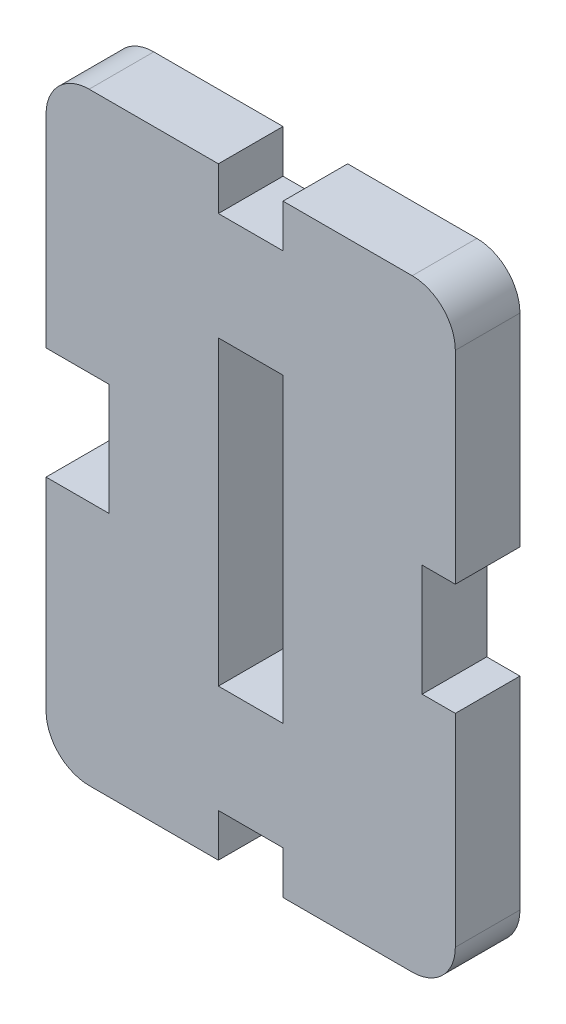
SolidWorks part; units mm, degrees
ref_plane "Front" through (0, 0, 0) normal (0, 0, 1) x (1, 0, 0)
ref_plane "Top" through (0, 0, 0) normal (0, 1, 0) x (1, 0, 0)
ref_plane "Right" through (0, 0, 0) normal (1, 0, 0) x (0, 0, -1)
sketch "Sketch1" plane through (0, 0, 0) normal (0, 0, 1) x (1, 0, 0)
  line L0 (-1044.1169, 48.9977) -> (-1044.1169, 34.9977)
  line L1 (-1049.1904, 41.9977) -> (-1034.6577, 41.9977) construction
  line L2 (-1041.1169, 34.9977) -> (-1041.1169, 48.9977)
  line L3 (-1041.1169, 48.9977) -> (-1044.1169, 48.9977)
  line L4 (-1033.1169, 53.9977) -> (-1033.1169, 44.5931)
  line L5 (-1033.1169, 44.5931) -> (-1034.6577, 44.5931)
  line L6 (-1034.6577, 44.5931) -> (-1034.6577, 39.4024)
  line L7 (-1050.1169, 27.9977) -> (-1044.1169, 27.9977)
  line L8 (-1042.6169, 53.9977) -> (-1041.1169, 53.9977)
  line L9 (-1041.1169, 53.9977) -> (-1041.1169, 55.9977)
  line L10 (-1041.1169, 55.9977) -> (-1035.1169, 55.9977)
  line L11 (-1042.6169, 53.9977) -> (-1044.1169, 53.9977)
  line L12 (-1044.1169, 53.9977) -> (-1044.1169, 55.9977)
  line L13 (-1052.1169, 39.4024) -> (-1052.1169, 29.9977)
  line L14 (-1049.1904, 39.4024) -> (-1052.1169, 39.4024)
  line L15 (-1044.1169, 29.9977) -> (-1044.1169, 27.9977)
  line L16 (-1042.6169, 29.9977) -> (-1044.1169, 29.9977)
  line L17 (-1041.1169, 27.9977) -> (-1035.1169, 27.9977)
  line L18 (-1049.1904, 39.4024) -> (-1049.1904, 44.5931)
  line L19 (-1049.1904, 44.5931) -> (-1052.1169, 44.5931)
  line L20 (-1052.1169, 44.5931) -> (-1052.1169, 53.9977)
  line L21 (-1041.1169, 29.9977) -> (-1041.1169, 27.9977)
  line L22 (-1042.6169, 29.9977) -> (-1041.1169, 29.9977)
  line L23 (-1033.1169, 39.4024) -> (-1034.6577, 39.4024)
  line L24 (-1050.1169, 55.9977) -> (-1044.1169, 55.9977)
  line L25 (-1033.1169, 29.9977) -> (-1033.1169, 39.4024)
  line L26 (-1041.1169, 34.9977) -> (-1044.1169, 34.9977)
  arc A0 (-1052.1169, 53.9977) -> (-1050.1169, 55.9977) centre (-1050.1169, 53.9977) cw
  arc A1 (-1033.1169, 53.9977) -> (-1035.1169, 55.9977) centre (-1035.1169, 53.9977) ccw
  arc A2 (-1033.1169, 29.9977) -> (-1035.1169, 27.9977) centre (-1035.1169, 29.9977) cw
  arc A3 (-1052.1169, 29.9977) -> (-1050.1169, 27.9977) centre (-1050.1169, 29.9977) ccw
  point P8 (-1044.1169, 41.9977)
  point P38 (-1041.1169, 41.9977)
  dimension "D1" = 2
  dimension "D2" = 3
  dimension "D3" = 8
  dimension "D4" = 8
  dimension "D5" = 14
  dimension "D6" = 2
  dimension "D7" = 28
extrude "Base-Extrude" add sketch "Sketch1" along normal blind 3
